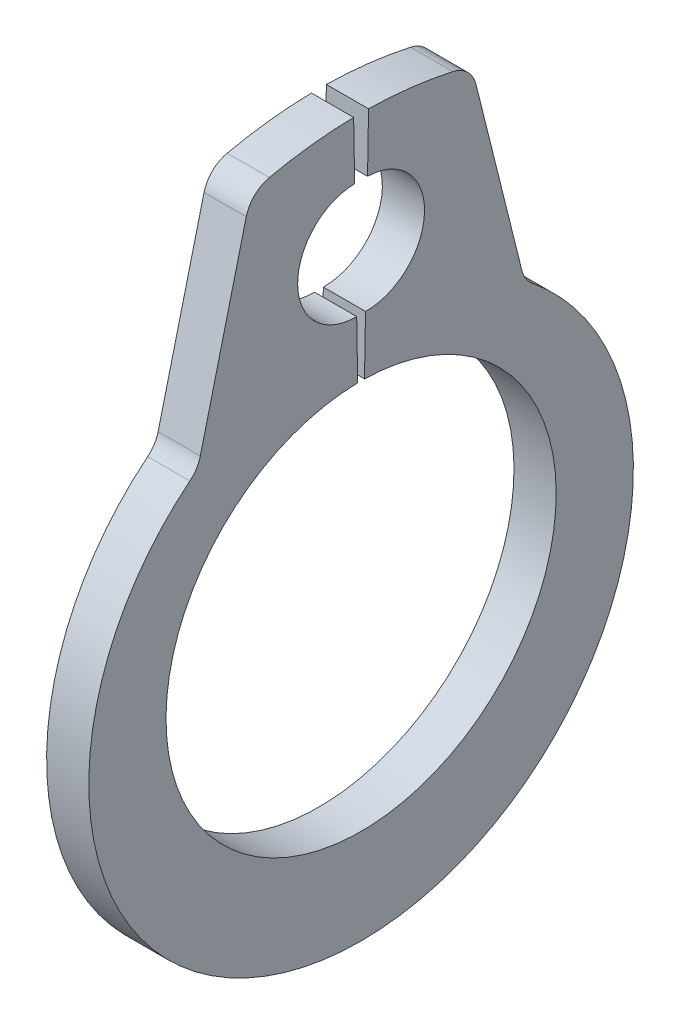
SolidWorks part; units mm, degrees
material "Cast Carbon Steel"
ref_plane "Front" through (0, 0, 0) normal (0, 0, 1) x (1, 0, 0)
ref_plane "Top" through (0, 0, 0) normal (0, 1, 0) x (1, 0, 0)
ref_plane "Right" through (0, 0, 0) normal (1, 0, 0) x (0, 0, -1)
sketch "Sketch1" plane through (0, 0, 0) normal (1, 0, 0) x (0, 0, -1)
  line L0 (0, 0) -> (0, 1.85) construction
  line L1 (-0.0323, 1.8497) -> (-0.0707, 4.0494) construction
  line L2 (-0.0707, 4.0494) -> (-1.0167, 4.0329) construction
  line L3 (-1.0167, 4.0329) -> (-1.549, 1.8982) construction
  line L4 (0.0707, 4.0494) -> (0.0323, 1.8497) construction
  line L5 (0.0707, 4.0494) -> (1.0167, 4.0329) construction
  line L6 (1.0167, 4.0329) -> (1.549, 1.8982) construction
  line L7 (-1.549, 1.8982) -> (-1.1696, 1.4333) construction
  line L8 (1.549, 1.8982) -> (1.1696, 1.4333) construction
  line L9 (0, -1.85) -> (0, -2.75) construction
  line L10 (-1.0167, 4.0329) -> (-0.0323, 1.8497) construction
  line L11 (0.0323, 1.8497) -> (0.0419, 2.3996)
  line L12 (0, 1.85) -> (0, 4.05) construction
  line L13 (1.0468, 3.9124) -> (1.549, 1.8982)
  line L14 (-1.0468, 3.9124) -> (-1.549, 1.8982)
  line L16 (0.0611, 3.4995) -> (0.0707, 4.0494)
  line L17 (-0.0611, 3.4995) -> (-0.0707, 4.0494)
  line L18 (-0.0419, 2.3996) -> (-0.0323, 1.8497)
  circle A0 centre (0, 0) radius 1.85 construction
  arc A1 (-0.0323, 1.8497) -> (0.0323, 1.8497) centre (0, 0) ccw
  circle A2 centre (0, -0.1678) radius 2.5822 construction
  arc A3 (0.0611, 3.4995) -> (0.0419, 2.3996) centre (0.0515, 2.9496) cw
  arc A4 (-0.0419, 2.3996) -> (-0.0611, 3.4995) centre (-0.0515, 2.9496) cw
  arc A6 (-1.549, 1.8982) -> (1.549, 1.8982) centre (0, -0.1678) ccw
  arc A7 (0.0707, 4.0494) -> (1.0468, 3.9124) centre (0, 0) cw
  arc A8 (-0.0707, 4.0494) -> (-1.0468, 3.9124) centre (0, 0) ccw
  dimension "A" = 3.7
  dimension "Smin" = 0.6
  dimension "D1" = 75
  dimension "Angle" = 1
  dimension "H" = 2.2
  dimension "D2" = 1.1
extrude "Extrude1" add sketch "Sketch1" along normal mid plane 0.4
fillet "Fillet1" radius 0.29 4 edges at (0, 1.8982, 1.549) (0, 3.9124, 1.0468) (0, 3.9124, -1.0468) (0, 1.8982, -1.549)
sketch "Sketch2" plane through (0, 0, 0) normal (0, 0, 1) x (1, 0, 0)
  line L0 (-1.25, 0) -> (3.75, 0)
  line L1 (3.75, 0) -> (3.75, -2)
  line L2 (-0.25, -2) -> (-1.15, -2)
  line L3 (3.75, -2) -> (0.25, -2)
  line L4 (0.25, -2) -> (0.25, -1.9)
  line L5 (0.25, -1.9) -> (-0.25, -1.9)
  line L6 (-0.25, -1.9) -> (-0.25, -2)
  line L7 (-0.25, -2) -> (-1.25, -2) construction
  line L8 (-1.25, -2) -> (-1.25, 0) construction
  line L9 (0, -1.9) -> (0, 0) construction
  line L10 (3.75, 0) -> (14.0551, 0) construction
  line L11 (-1.15, -2) -> (-1.25, -1.9)
  line L12 (-1.25, -1.9) -> (-1.25, 0)
  dimension "D2" = 5
  dimension "D3" = 1.25
  dimension "D1" = 45
revolve "Revolve1" [suppressed] add sketch "Sketch2" angle 360 about L10
equation "\"D2@Sketch2\" = \"W@Sketch2\"*10"
equation "\"D3@Sketch2\" = \"D2@Sketch2\"/4"
equation "\"Smin@Sketch1\" = \"Smax@Sketch1\"/1.5"
equation "\"D2@Sketch1\" = \"H@Sketch1\"/2"
